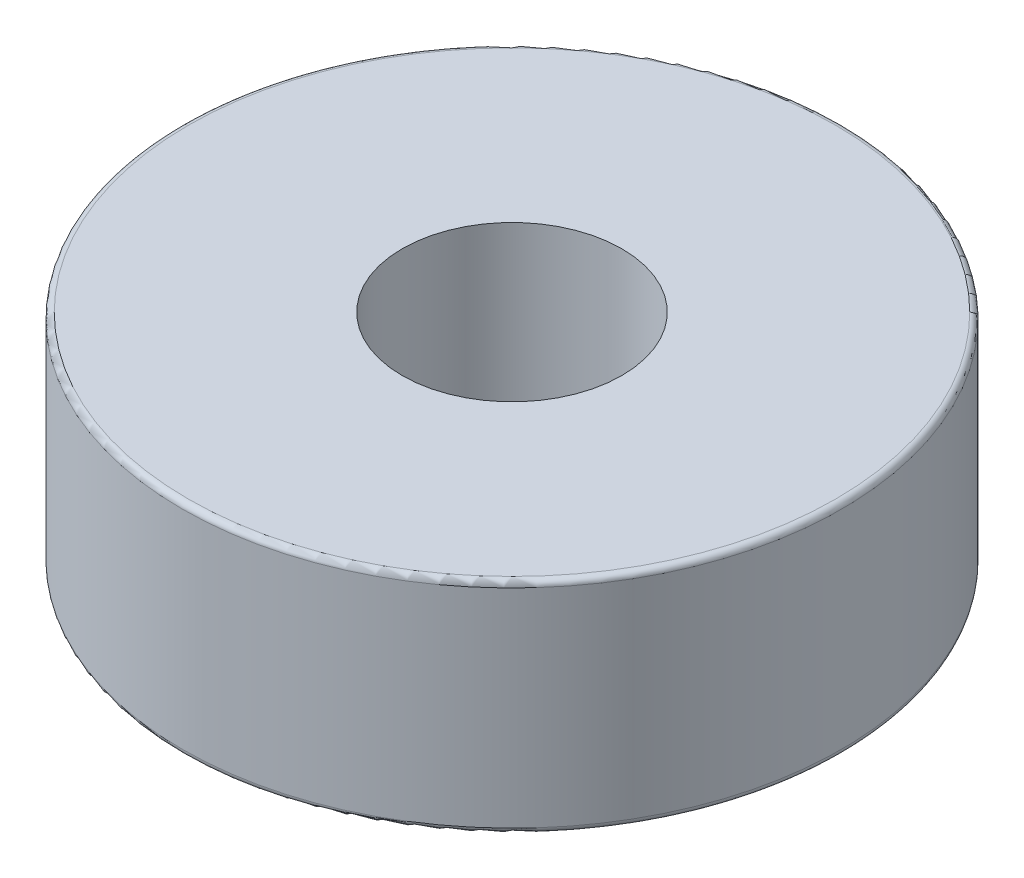
SolidWorks part; units mm, degrees
material "Cast Alloy Steel"
ref_plane "Front Plane" through (0, 0, 0) normal (0, 0, 1) x (1, 0, 0)
ref_plane "Top Plane" through (0, 0, 0) normal (0, 1, 0) x (1, 0, 0)
ref_plane "Right Plane" through (0, 0, 0) normal (1, 0, 0) x (0, 0, -1)
sketch "Sketch1" plane through (0, 0, 0) normal (0, -1, 0) x (1, 0, 0)
  circle A0 centre (0, 0) radius 4.7625
  circle A1 centre (0, 0) radius 14.2875
  dimension "D1" = 9.525
  dimension "D2" = 28.575
extrude "Boss-Extrude1" add sketch "Sketch1" against normal blind 9.525
fillet "Fillet1" radius 0.254 2 edges at (0, 9.525, 14.2875) (0, 0, 14.2875)
